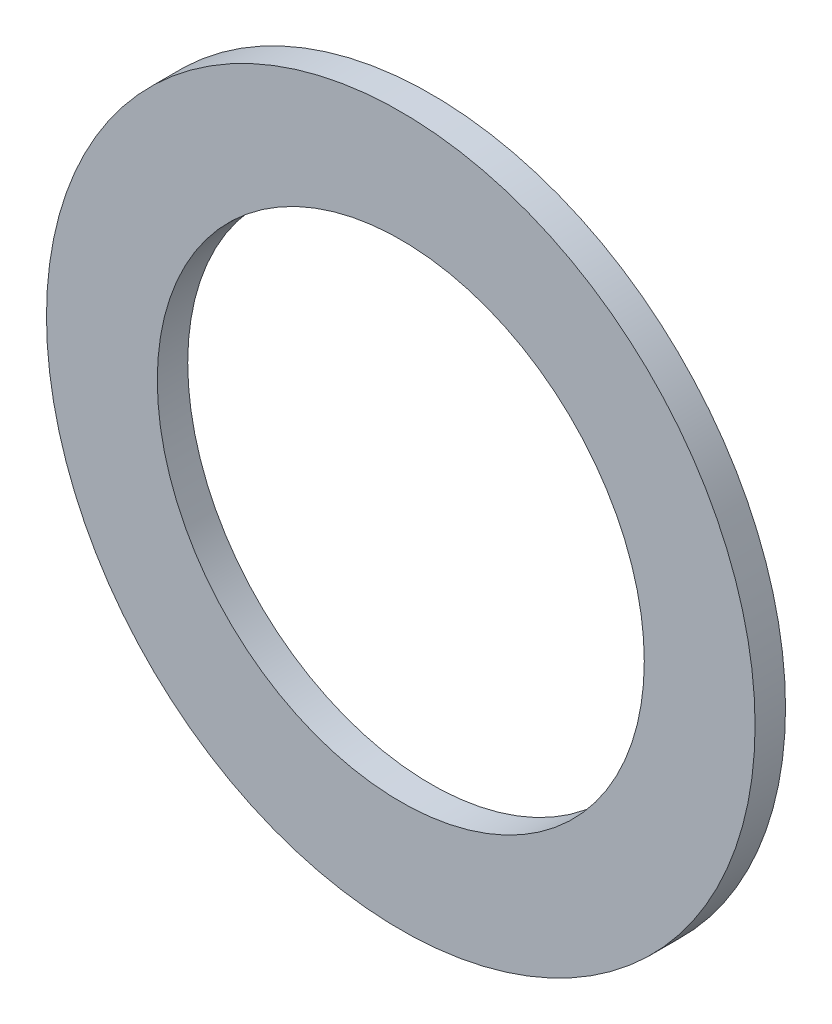
SolidWorks part; units mm, degrees
ref_plane "Plan de face" through (0, 0, 0) normal (0, 0, 1) x (1, 0, 0)
ref_plane "Plan de dessus" through (0, 0, 0) normal (0, 1, 0) x (1, 0, 0)
ref_plane "Plan de droite" through (0, 0, 0) normal (1, 0, 0) x (0, 0, -1)
sketch "Esquisse1" plane through (0, 0, 0) normal (0, 0, 1) x (1, 0, 0)
  circle A0 centre (0, 0) radius 73.914
  circle A1 centre (0, 0) radius 50.8
  dimension "D1" = 147.828
  dimension "D2" = 101.6
extrude "Boss.-Extru.1" add sketch "Esquisse1" along normal blind 6.35
